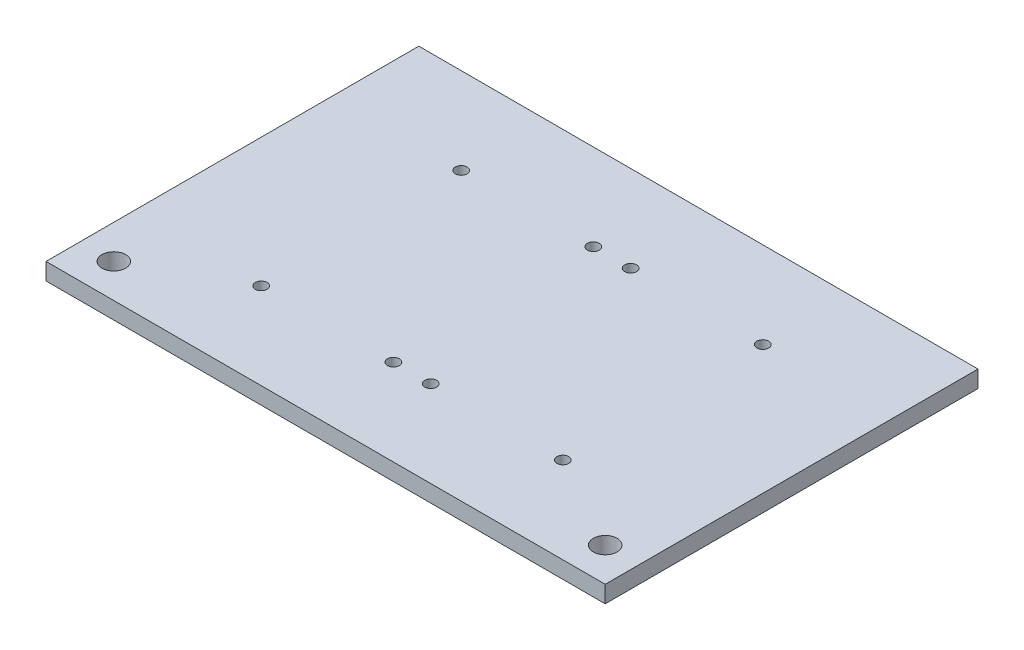
SolidWorks part; units mm, degrees
ref_plane "Front Plane" through (0, 0, 0) normal (0, 0, 1) x (1, 0, 0)
ref_plane "Top Plane" through (0, 0, 0) normal (0, 1, 0) x (1, 0, 0)
ref_plane "Right Plane" through (0, 0, 0) normal (1, 0, 0) x (0, 0, -1)
sketch "Sketch1" plane through (0, 0, 0) normal (0, 1, 0) x (1, 0, 0)
  line L0 (82.5, 55) -> (-82.5, 55)
  line L2 (-82.5, 55) -> (-82.5, -55)
  line L3 (-82.5, -55) -> (82.5, -55)
  line L4 (82.5, 55) -> (82.5, -55)
  line L5 (-82.5, 55) -> (82.5, -55) construction
  line L6 (-82.5, -55) -> (82.5, 55) construction
  line L7 (44.5, -29.5) -> (5.5, -29.5) construction
  line L8 (44.5, -29.5) -> (44.5, 29.5) construction
  line L9 (44.5, 29.5) -> (5.5, 29.5) construction
  line L10 (5.5, -29.5) -> (5.5, 29.5) construction
  line L11 (44.5, -29.5) -> (5.5, 29.5) construction
  line L12 (44.5, 29.5) -> (5.5, -29.5) construction
  circle A0 centre (72.5, -45) radius 3.5
  circle A1 centre (-72.5, -45) radius 3.5
  circle A2 centre (44.5, -29.5) radius 1.75
  circle A3 centre (5.5, -29.5) radius 1.75
  circle A12 centre (5.5, 29.5) radius 1.75
  circle A13 centre (44.5, 29.5) radius 1.75
  circle A18 centre (-5.5, -29.5) radius 1.75
  circle A19 centre (-44.5, -29.5) radius 1.75
  circle A20 centre (-44.5, 29.5) radius 1.75
  circle A21 centre (-5.5, 29.5) radius 1.75
  point P0 (0, 0)
  point P10 (25, 0)
  point P15 (-45, 30)
  point P16 (-45, -30)
  point P17 (0, 0)
  dimension "D3" = 7
  dimension "D10" = 3.5
  dimension "D1" = 110
  dimension "D2" = 165
  dimension "D4" = 10
  dimension "D5" = 10
  dimension "D6" = 10
  dimension "D7" = 59
  dimension "D8" = 39
  dimension "D9" = 2
  dimension "D11" = 5.5
  dimension "D12" = 11
extrude "Boss-Extrude1" add sketch "Sketch1" along normal blind 5
